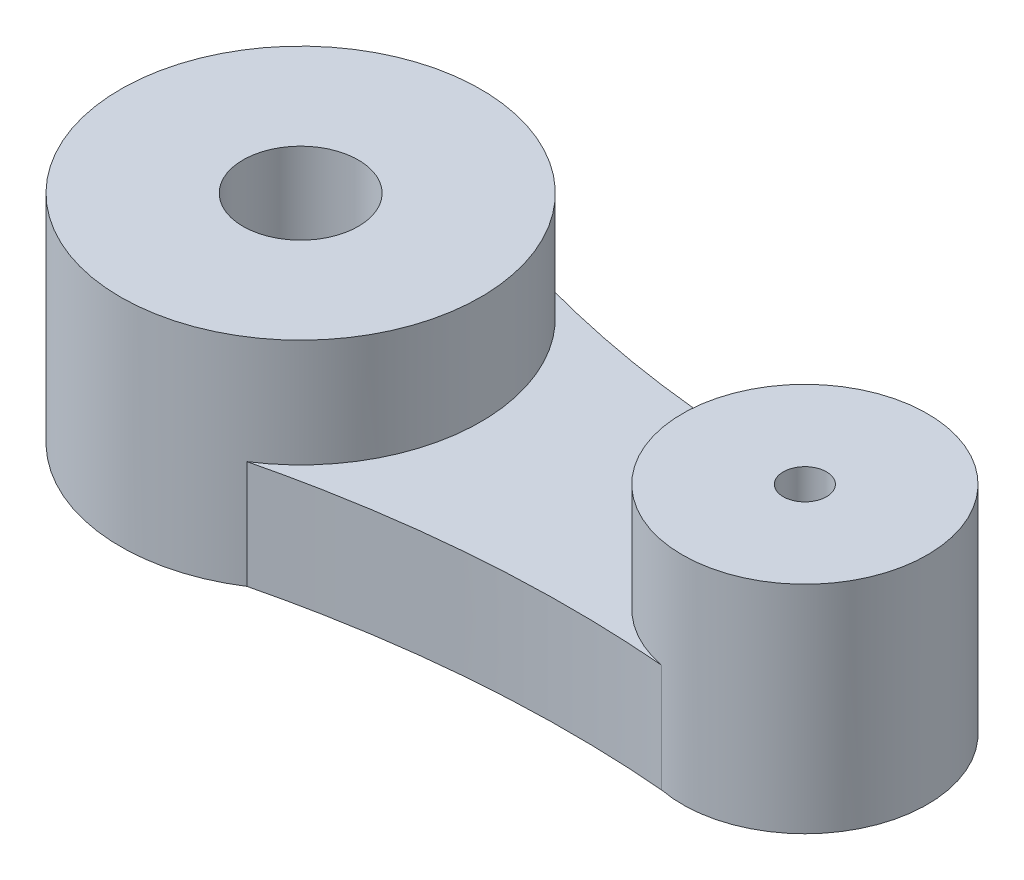
SolidWorks part; units mm, degrees
ref_plane "Płaszczyzna przednia" through (0, 0, 0) normal (0, 0, 1) x (1, 0, 0)
ref_plane "Płaszczyzna górna" through (0, 0, 0) normal (0, 1, 0) x (1, 0, 0)
ref_plane "Płaszczyzna prawa" through (0, 0, 0) normal (1, 0, 0) x (0, 0, -1)
sketch "Szkic1" plane through (0, 0, 0) normal (0, 1, 0) x (1, 0, 0)
  line L0 (0, 0) -> (27.5, 0) construction
  circle A0 centre (0, 0) radius 12.5
  circle A1 centre (27.5, 0) radius 6
  dimension "D1" = 25
  dimension "D3" = 12
  dimension "D2" = 27.5
extrude "Dodanie-wyciągnięcie2" add sketch "Szkic1" along normal blind 15 contours A0
sketch "Szkic3" plane through (0, 0, 0) normal (0, 1, 0) x (1, 0, 0)
  line L0 (0, 0) -> (35, 0) construction
  circle A0 centre (35, 0) radius 8.5
  dimension "D2" = 17
  dimension "D1" = 35
extrude "Dodanie-wyciągnięcie3" add sketch "Szkic3" along normal blind 15 separate body
sketch "Szkic4" plane through (0, 0, 0) normal (0, -1, 0) x (-1, 0, 0)
  line L0 (0, 0) -> (-35, 0) construction
  arc A0 (-6.7789, 10.5022) -> (-6.7789, -10.5022) centre (0, 0) ccw
  arc A2 (-32.953, 8.2498) -> (-33.4113, -8.3502) centre (-35, 0) cw
  spline S0 degree 2 poles (-6.7789, -10.5022) (-20.2255, -7.2395) (-33.4113, -8.3502) knots 0 0 0 0.631379 0.631379 0.631379
  spline S1 degree 2 poles (-6.7789, 10.5022) (-20.0781, 6.8774) (-32.953, 8.2498) knots 0 0 0 0.617827 0.617827 0.617827
extrude "Dodanie-wyciągnięcie4" add sketch "Szkic4" against normal blind 7.5
hole_wizard "Otwory ustalające Ø8.0mm1" positions "Szkic5" profile "Szkic6" hole size "Ø8.0" standard "Ansi Metric" end condition through all
sketch "Szkic5" plane through (0, 15, 0) normal (0, 1, 0) x (1, 0, 0)
  point P0 (0, 0)
sketch "Szkic6" plane through (0, 15, 0) normal (1, 0, 0) x (0, 0, 1)
  line L0 (0, 0) -> (0, 15)
  line L1 (0, 15) -> (4, 15)
  line L2 (4, 15) -> (4, 0)
  line L5 (4, 0) -> (0, 0)
  line L11 (0, -6.35) -> (0, 107.95) construction
  dimension "Średnica otworu na wylot" = 8
  dimension "Głębokość otworu na wylot" = 15
hole_wizard "Otwory ustalające Ø3.0mm2" positions "Szkic13" profile "Szkic14" hole size "Ø3.0" standard "Ansi Metric" end condition through all
sketch "Szkic13" plane through (0, 15, 0) normal (0, 1, 0) x (1, 0, 0)
  point P0 (35, 0)
sketch "Szkic14" plane through (35, 15, 0) normal (1, 0, 0) x (0, 0, 1)
  line L0 (0, 0) -> (0, 15)
  line L1 (0, 15) -> (1.5, 15)
  line L2 (1.5, 15) -> (1.5, 0)
  line L5 (1.5, 0) -> (0, 0)
  line L11 (0, -6.35) -> (0, 107.95) construction
  dimension "Średnica otworu na wylot" = 3
  dimension "Głębokość otworu na wylot" = 15
